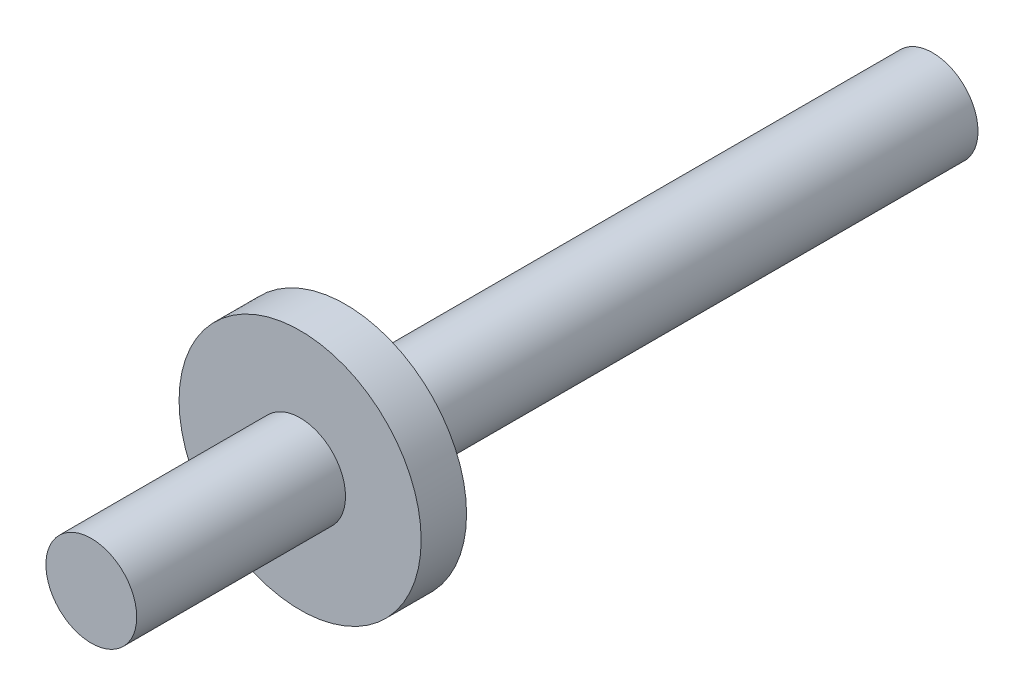
SolidWorks part; units mm, degrees
material "Brass"
ref_plane "Front Plane" through (0, 0, 0) normal (0, 0, 1) x (1, 0, 0)
ref_plane "Top Plane" through (0, 0, 0) normal (0, 1, 0) x (1, 0, 0)
ref_plane "Right Plane" through (0, 0, 0) normal (1, 0, 0) x (0, 0, -1)
sketch "Sketch1" plane through (0, 0, 0) normal (0, 0, 1) x (1, 0, 0)
  circle A0 centre (75, -1230.027) radius 40
  arc A1 (114.5715, -1235.866) -> (35.4285, -1235.866) centre (75, -1230.027) ccw construction
extrude "Boss-Extrude1" add sketch "Sketch1" along normal blind 15
sketch "Sketch2" plane through (0, 0, 15) normal (0, 0, 1) x (1, 0, 0)
  circle A0 centre (75, -1230.027) radius 15
  circle A1 centre (75, -1230.027) radius 40 construction
  dimension "D1" = 30
extrude "Boss-Extrude2" add sketch "Sketch2" along normal blind 69 and the other way blind 209
